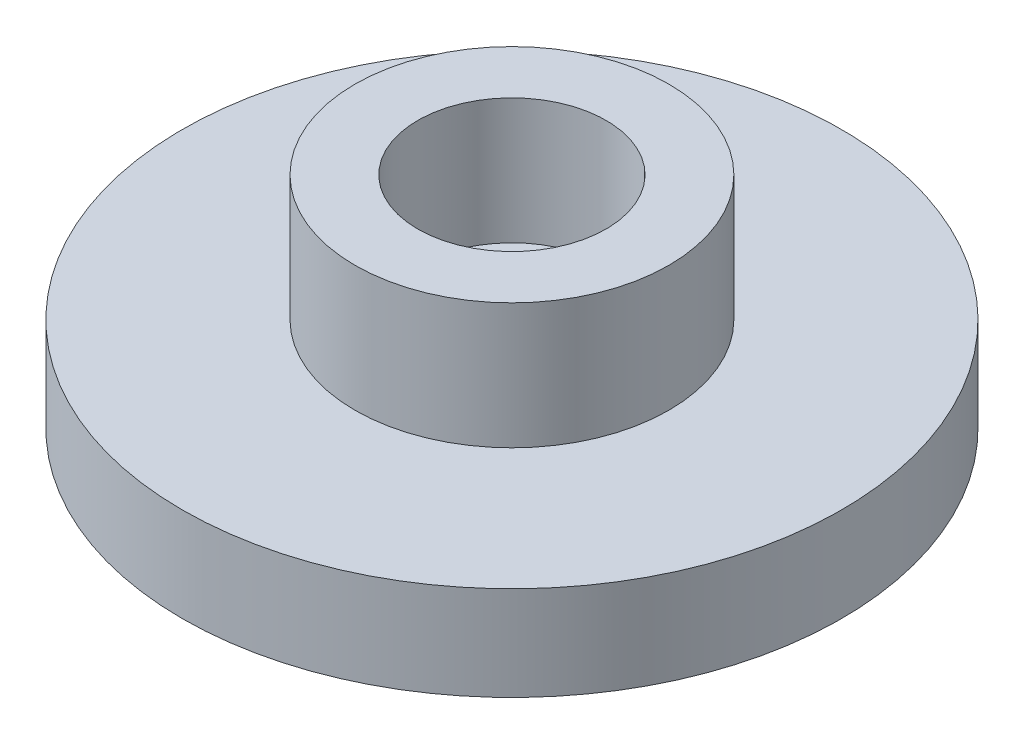
SolidWorks part; units mm, degrees
ref_plane "Front Plane" through (0, 0, 0) normal (0, 0, 1) x (1, 0, 0)
ref_plane "Top Plane" through (0, 0, 0) normal (0, 1, 0) x (1, 0, 0)
ref_plane "Right Plane" through (0, 0, 0) normal (1, 0, 0) x (0, 0, -1)
sketch "Sketch1" plane through (0, 0, 0) normal (0, 1, 0) x (1, 0, 0)
  circle A0 centre (0, 0) radius 10.5
  dimension "D1" = 21
extrude "Boss-Extrude1" add sketch "Sketch1" along normal blind 3
sketch "Sketch2" plane through (0, 3, 0) normal (0, 1, 0) x (1, 0, 0)
  circle A0 centre (0, 0) radius 5
  dimension "D1" = 10
extrude "Boss-Extrude2" add sketch "Sketch2" along normal blind 4
sketch "Sketch3" plane through (0, 7, 0) normal (0, 1, 0) x (1, 0, 0)
  circle A0 centre (0, 0) radius 3
  dimension "D1" = 6
extrude "Cut-Extrude1" cut sketch "Sketch3" against normal blind 4
